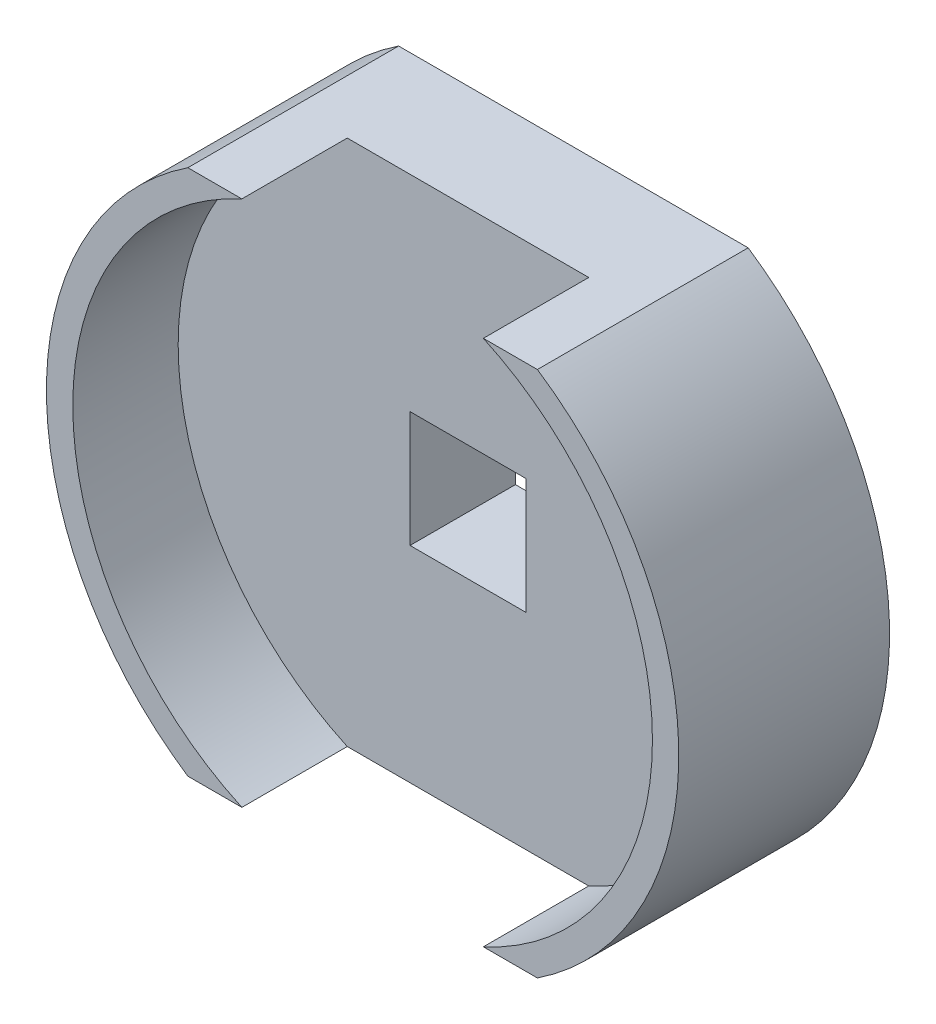
SolidWorks part; units mm, degrees
ref_plane "Ebene vorne" through (0, 0, 0) normal (0, 0, 1) x (1, 0, 0)
ref_plane "Ebene oben" through (0, 0, 0) normal (0, 1, 0) x (1, 0, 0)
ref_plane "Ebene rechts" through (0, 0, 0) normal (1, 0, 0) x (0, 0, -1)
sketch "Sketch1" plane through (0, 0, 0) normal (0, 0, 1) x (1, 0, 0)
  circle A0 centre (0, 0) radius 6
  dimension "D1" = 12
extrude "Boss-Extrude1" add sketch "Sketch1" along normal blind 2
sketch "Sketch2" plane through (0, 0, 2) normal (0, 0, 1) x (1, 0, 0)
  circle A0 centre (0, 0) radius 6
  circle A1 centre (0, 0) radius 5.5
  dimension "D1" = 11
  dimension "D2" = 12
extrude "Boss-Extrude2" add sketch "Sketch2" along normal blind 2
sketch "Sketch7" plane through (0, 0, 0) normal (0, 0, 1) x (1, 0, 0)
  line L1 (-10, 5) -> (10, 5)
  line L2 (-10, 5) -> (-10, -5)
  line L3 (-10, -5) -> (10, -5)
  line L4 (10, 5) -> (10, -5)
  line L5 (-10, 5) -> (10, -5) construction
  line L6 (-10, -5) -> (10, 5) construction
  line L7 (-12, 6) -> (12, 6)
  line L8 (-12, 6) -> (-12, -6)
  line L9 (-12, -6) -> (12, -6)
  line L10 (12, 6) -> (12, -6)
  line L11 (-12, 6) -> (12, -6) construction
  line L12 (-12, -6) -> (12, 6) construction
  point P0 (0, 0)
  point P6 (0, 0)
  dimension "D1" = 20
  dimension "D2" = 10
  dimension "D3" = 12
  dimension "D4" = 24
extrude "Cut-Extrude1" cut sketch "Sketch7" along normal blind 6
sketch "Sketch4" plane through (0, 0, 0) normal (0, 0, 1) x (1, 0, 0)
  line L1 (-1.1, 1.1) -> (1.1, 1.1)
  line L2 (-1.1, 1.1) -> (-1.1, -1.1)
  line L3 (-1.1, -1.1) -> (1.1, -1.1)
  line L4 (1.1, 1.1) -> (1.1, -1.1)
  line L5 (-1.1, 1.1) -> (1.1, -1.1) construction
  line L6 (-1.1, -1.1) -> (1.1, 1.1) construction
  point P0 (0, 0)
  dimension "D1" = 2.2
  dimension "D2" = 2.2
extrude "Cut-Extrude2" cut sketch "Sketch4" along normal blind 2
